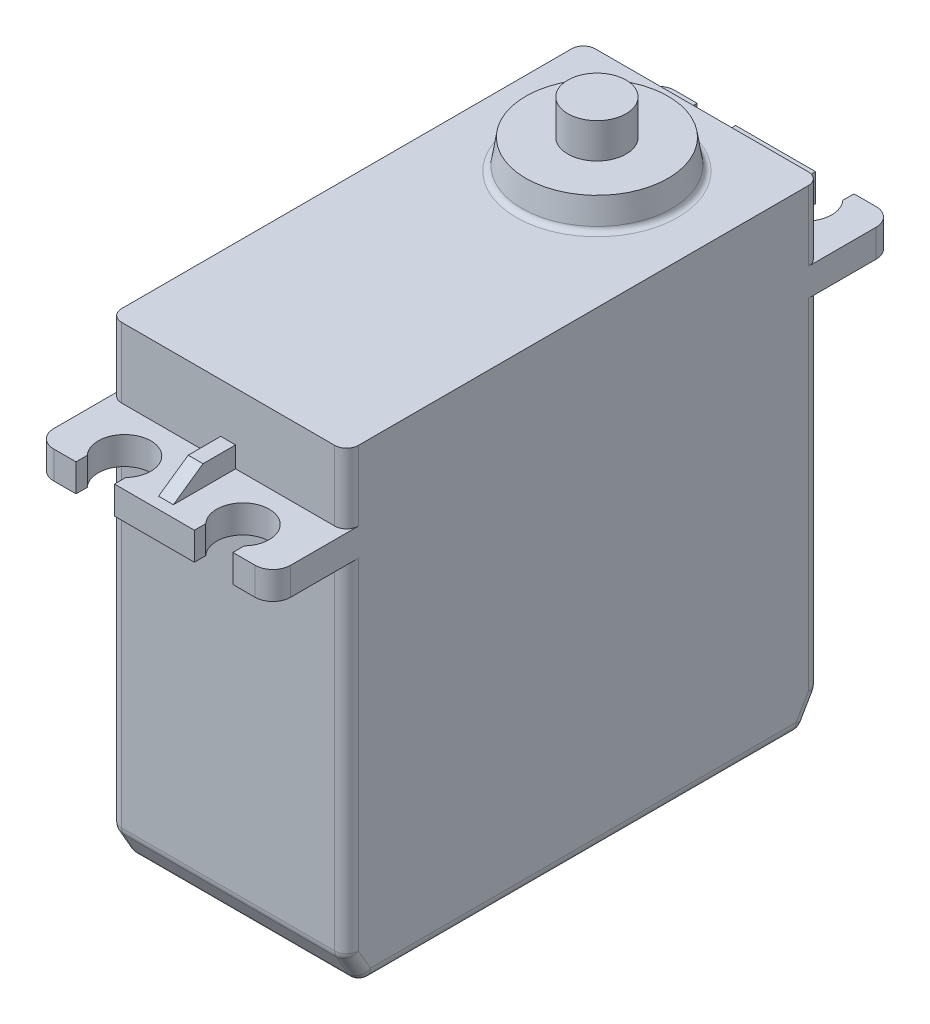
SolidWorks part; units mm, degrees
ref_plane "Front Plane" through (0, 0, 0) normal (0, 0, 1) x (1, 0, 0)
ref_plane "Top Plane" through (0, 0, 0) normal (0, 1, 0) x (1, 0, 0)
ref_plane "Right Plane" through (0, 0, 0) normal (1, 0, 0) x (0, 0, -1)
sketch "Sketch1" plane through (0, 0, 0) normal (0, 1, 0) x (1, 0, 0)
  line L1 (-10.16, 10.16) -> (10.16, 10.16)
  line L2 (-10.16, 10.16) -> (-10.16, -30.48)
  line L3 (-10.16, -30.48) -> (10.16, -30.48)
  line L4 (10.16, 10.16) -> (10.16, -30.48)
  dimension "D1" = 20.32
  dimension "D2" = 40.64
  dimension "D3" = 10.16
  dimension "D4" = 10.16
extrude "Extrude1" add sketch "Sketch1" along normal blind 32
sketch "Sketch2" plane through (0, 32, 0) normal (0, 1, 0) x (-1, 0, 0)
  line L0 (10.16, 30.48) -> (10.16, 36.8046)
  line L1 (10.16, 36.8046) -> (6.731, 36.8046)
  line L2 (-10.16, 36.8046) -> (-10.16, 30.48)
  line L3 (10.16, -10.16) -> (10.16, -16.4846)
  line L4 (10.16, -10.16) -> (10.16, 30.48)
  line L5 (10.16, 30.48) -> (-10.16, 30.48)
  line L6 (-10.16, 30.48) -> (-10.16, -10.16)
  line L7 (-10.16, -10.16) -> (10.16, -10.16)
  line L8 (10.16, -10.16) -> (10.16, 30.48)
  line L9 (10.16, 30.48) -> (-10.16, 30.48)
  line L10 (-10.16, 30.48) -> (-10.16, -10.16)
  line L11 (-10.16, -10.16) -> (10.16, -10.16)
  line L12 (10.16, -16.4846) -> (6.731, -16.4846)
  line L13 (-10.16, -16.4846) -> (-10.16, -10.16)
  line L14 (-6.731, 35.8342) -> (-6.731, 36.8046)
  line L15 (-3.429, 35.8342) -> (-3.429, 36.8046)
  line L16 (3.429, 35.8342) -> (3.429, 36.8046)
  line L17 (6.731, 35.8342) -> (6.731, 36.8046)
  line L18 (6.731, -15.5142) -> (6.731, -16.4846)
  line L19 (3.429, -15.5142) -> (3.429, -16.4846)
  line L20 (-3.429, -15.5142) -> (-3.429, -16.4846)
  line L21 (-6.731, -15.5142) -> (-6.731, -16.4846)
  line L22 (-6.731, -16.4846) -> (-10.16, -16.4846)
  line L23 (3.429, -16.4846) -> (-3.429, -16.4846)
  line L24 (-6.731, 36.8046) -> (-10.16, 36.8046)
  line L25 (3.429, 36.8046) -> (-3.429, 36.8046)
  arc A0 (3.429, 35.8342) -> (6.731, 35.8342) centre (5.08, 34.29) ccw
  arc A1 (-6.731, 35.8342) -> (-3.429, 35.8342) centre (-5.08, 34.29) ccw
  arc A2 (-3.429, -15.5142) -> (-6.731, -15.5142) centre (-5.08, -13.97) ccw
  arc A3 (6.731, -15.5142) -> (3.429, -15.5142) centre (5.08, -13.97) ccw
  line M5 (10.16, -10.16) -> (10.16, 30.48)
  line M6 (10.16, 30.48) -> (-10.16, 30.48)
  line M7 (-10.16, 30.48) -> (-10.16, -10.16)
  line M8 (-10.16, -10.16) -> (10.16, -10.16)
  dimension "D2" = 4.5212
  dimension "D9" = 3.302
  dimension "D3" = 5.08
  dimension "D4" = 10.16
  dimension "D5" = 48.26
  dimension "D6" = 3.81
  dimension "D7" = 6.3246
  dimension "D8" = 6.3246
  dimension "D10" = 3.302
  dimension "D11" = 1.651
  dimension "D12" = 1.651
  dimension "D1" = 0
extrude "Extrude2" add sketch "Sketch2" along normal blind 2.3813 contours M8 M5 M6 M7 | A3 L18 L12 L3 L13 L22 L21 A2 L20 L23 L19 M8 | A1 L14 L24 L2 L0 L1 L17 A0 L16 L25 L15 M6
sketch "Sketch3" plane through (0, 34.3813, 0) normal (0, 1, 0) x (-1, 0, 0)
  line L4 (10.16, -10.16) -> (10.16, 30.48)
  line L5 (-10.16, -10.16) -> (10.16, -10.16)
  line L6 (-10.16, 30.48) -> (-10.16, -10.16)
  line L7 (10.16, 30.48) -> (-10.16, 30.48)
  line L8 (10.16, -10.16) -> (10.16, 30.48)
  line L9 (-10.16, -10.16) -> (10.16, -10.16)
  line L10 (-10.16, 30.48) -> (-10.16, -10.16)
  line L11 (10.16, 30.48) -> (-10.16, 30.48)
  dimension "D1" = 0
extrude "Extrude3" add sketch "Sketch3" along normal blind 6
ref_plane "Plane1" through (0, 38.1, 0) normal (0, -1, 0) x (1, 0, 0)
sketch "Sketch7" plane through (0, 0, 0) normal (1, 0, 0) x (0, 0, -1)
  line L0 (15.494, 34.3813) -> (12.954, 36.1593)
  line L4 (12.954, 36.1593) -> (10.16, 36.1593)
  line L5 (10.16, 40.3813) -> (10.16, 34.3813) construction
  line L6 (16.4846, 34.3813) -> (10.16, 34.3813) construction
  line L7 (10.16, 36.1593) -> (10.16, 34.3813)
  line L8 (10.16, 34.3813) -> (15.494, 34.3813)
  dimension "D1" = 1.778
  dimension "D2" = 2.794
  dimension "D3" = 5.334
extrude "Extrude6" add sketch "Sketch7" along normal mid plane 1.27
ref_plane "Plane2" through (0, 0, 10.16) normal (0, 0, -1) x (-1, 0, 0)
mirror "Mirror1" about plane through (0, 0, 10.16) normal (0, 0, -1) of "Extrude6"
chamfer "Chamfer2" distance 2.54 angle 30 2 edges at (0, 0, 30.48) (0, 0, -10.16)
fillet "Fillet1" radius 1.016 18 edges at (10.16, 0, 10.16) (10.16, 1.27, -9.4268) (0, 0, -8.6935) (0, 2.54, -10.16) (-10.16, 1.27, -9.4268) (10.16, 1.27, 29.7468) (0, 2.54, 30.48) (-10.16, 0, 10.16) (0, 0, 29.0135) (-10.16, 1.27, 29.7468)
fillet "Fillet2" radius 1.524 4 edges at (-10.16, 33.1906, 36.8046) (10.16, 33.1906, 36.8046) (-10.16, 33.1906, -16.4846) (10.16, 33.1906, -16.4846)
sketch "Sketch9" plane through (0, 0, -10.16) normal (0, 0, -1) x (-1, 0, 0)
  line L1 (-3.175, 12.54) -> (3.175, 12.54)
  line L2 (-3.175, 12.54) -> (-3.175, 10)
  line L3 (-3.175, 10) -> (3.175, 10)
  line L4 (3.175, 12.54) -> (3.175, 10)
  dimension "D1" = 6.35
  dimension "D2" = 2.54
  dimension "D3" = 10
  dimension "D4" = 3.175
extrude "Extrude8" add sketch "Sketch9" along normal blind 2.3813
sketch "Sketch10" plane through (0, 0, -12.5412) normal (0, 0, -1) x (-1, 0, 0)
  line L8 (-2.54, 11.905) -> (-2.54, 10.635)
  line L9 (-2.54, 10.635) -> (2.54, 10.635)
  line L10 (2.54, 10.635) -> (2.54, 11.905)
  line L11 (2.54, 11.905) -> (-2.54, 11.905)
  line L12 (-2.54, 11.905) -> (-2.54, 10.635)
  line L13 (-2.54, 10.635) -> (2.54, 10.635)
  line L14 (2.54, 10.635) -> (2.54, 11.905)
  line L15 (2.54, 11.905) -> (-2.54, 11.905)
  dimension "D1" = 0.635
extrude "Cut-Extrude1" cut sketch "Sketch10" against normal up to surface (2.3813 mm away) up to face at (2.286, 17.4061, -10.16)
sketch "Эскиз1" plane through (0, 40.3813, 0) normal (0, 1, 0) x (1, 0, 0)
  line L0 (9.144, 10.16) -> (0.635, 10.16) construction
  circle A0 centre (0, 1.16) radius 6.5
  dimension "D1" = 9
extrude "Вытянуть1" add sketch "Эскиз1" along normal blind 2.5 draft 9
fillet "Скругление1" radius 0.5 1 edges at (0, 40.3813, 5.34)
sketch "Эскиз2" plane through (0, 42.8813, 0) normal (0, 1, 0) x (1, 0, 0)
  circle A0 centre (0, 1.16) radius 2.5
extrude "Вытянуть2" add sketch "Эскиз2" along normal blind 3
